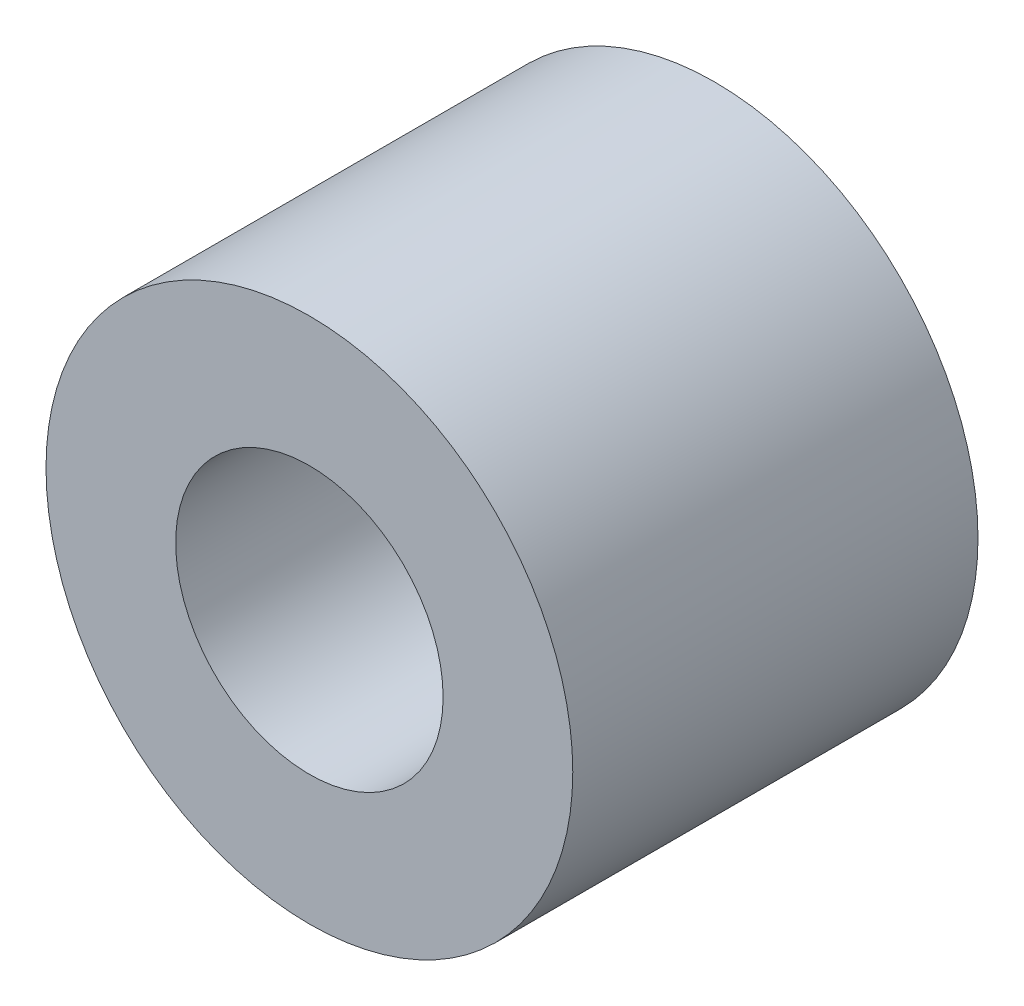
SolidWorks part; units mm, degrees
ref_plane "Front Plane" through (0, 0, 0) normal (0, 0, 1) x (1, 0, 0)
ref_plane "Top Plane" through (0, 0, 0) normal (0, 1, 0) x (1, 0, 0)
ref_plane "Right Plane" through (0, 0, 0) normal (1, 0, 0) x (0, 0, -1)
sketch "Sketch1" plane through (0, 0, 0) normal (0, 0, 1) x (1, 0, 0)
  circle A0 centre (0, 0) radius 3.25
  circle A1 centre (0, 0) radius 1.65
extrude "Boss-Extrude1" add sketch "Sketch1" along normal blind 5
